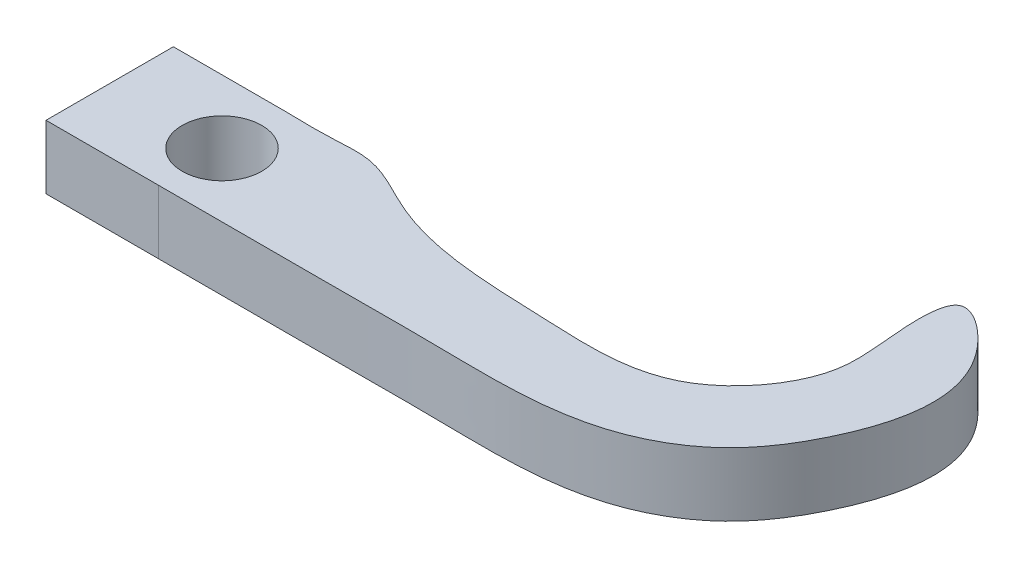
SolidWorks part; units mm, degrees
ref_plane "前视基准面" through (0, 0, 0) normal (0, 0, 1) x (1, 0, 0)
ref_plane "上视基准面" through (0, 0, 0) normal (0, 1, 0) x (1, 0, 0)
ref_plane "右视基准面" through (0, 0, 0) normal (1, 0, 0) x (0, 0, -1)
other "Configuration Table"
sketch "草图1" plane through (0, 0, 0) normal (0, 1, 0) x (1, 0, 0)
  line L0 (0, 4) -> (45, 4) construction
  line L1 (45, 4) -> (45, -4) construction
  line L2 (45, -4) -> (0, -4) construction
  line L3 (45, -4) -> (52.6082, -4) construction
  line L4 (52.6082, -4) -> (52.6082, 16) construction
  line L5 (52.6082, 16) -> (45, 16) construction
  line L6 (45, 16) -> (45, 4) construction
  line L7 (0, 4) -> (-7.0532, 4) construction
  line L8 (-7.0532, 4) -> (-7.0532, -4) construction
  line L9 (-7.0532, -4) -> (0, -4) construction
  line L10 (0, 4) -> (-7.0532, 4)
  line L11 (-7.0532, 4) -> (-7.0532, -4)
  line L12 (-7.0532, -4) -> (0, -4)
  circle A0 centre (0, 0) radius 2.5 construction
  circle A1 centre (0, 0) radius 4 construction
  circle A2 centre (0, 0) radius 2.5
  circle A3 centre (0, 0) radius 4
  spline S0 degree 3 poles (0, 4) (0.9652, 3.9779) (2.6763, 3.9388) (5.7483, 4.2351) (10.7984, 1.043) (18.4189, 0.9833) (27.4063, 0.4151) (31.8486, 6.5096) (31.1785, 10.599) (31.0094, 15.9203) (37.3084, 11.2163) (35.805, 4.5672) (32.4111, -0.6507) (26.4671, -4.264) (18.8603, -3.9418) (11.6431, -4.0066) (5.8074, -3.9976) (2.2358, -3.9991) (0, -4) knots 0 0 0 0 0.031523 0.055887 0.098002 0.21606 0.302294 0.373418 0.416617 0.454315 0.488953 0.591587 0.647126 0.690459 0.810546 0.883819 0.927272 1 1 1 1
  point P16 (18.9299, 2.8554)
  point P18 (9.6052, 4)
  point P20 (4.768, 4)
  point P22 (7.5071, 4)
  point P24 (13.1019, 3.2051)
  point P26 (21.4359, -4)
  point P28 (10.2462, -4)
  point P30 (17.0067, -4)
  point P32 (19.0464, 1.5733)
  point P33 (40.5688, 6.738)
  point P34 (26.3314, 1.6898)
  point P36 (30.8189, 7.9258)
  point P38 (34.6071, 16)
  point P40 (37.8125, 17.5419)
  point P42 (41.0178, 16.8425)
  point P44 (45, 11.4225)
  point P46 (40.174, 14.7334)
  point P47 (32.5734, 13.3515)
  point P48 (35.6334, 17.6947)
  point P49 (38.7921, 16)
  point P50 (37.9037, 9.8967)
  point P51 (35.2386, 2.5922)
  point P52 (30.5005, -1.4548)
  point P53 (28.1315, 2.2961)
  point P54 (33.1657, 15.8192)
  point P55 (35.557, 18.2531)
  point P56 (2.4354, 4)
  point P57 (4.6833, 4)
  point P58 (13.3113, 2.7055)
  point P59 (8.2865, 3.2674)
  point P60 (26.9309, 2.6393)
  point P61 (32.6131, 10.5376)
  point P62 (36.2093, 15.7527)
  point P63 (38.0138, 14.1437)
  point P64 (38.401, 7.4629)
  point P65 (37.764, 7.618)
  point P66 (31.2222, 11.189)
  point P67 (32.8184, 14.4783)
  point P68 (35.0919, 13.801)
  point P69 (36.4463, 7.1741)
  point P70 (35.4305, 12.6885)
  point P71 (0, 0)
  point P72 (33.2054, 15.349)
  point P73 (31.741, 14.6282)
  point P74 (36.3019, 5.9045)
  point P75 (34.4777, 12.9779)
  point P76 (36.153, 5.4578)
  point P77 (28.4934, -2.7921)
  point P78 (0, 0)
  point P79 (33.2224, 0.3529)
  point P80 (35.5495, 4.4673)
  point P81 (31.8841, -0.6738)
  point P82 (34.8354, 3.5153)
  dimension "D1" = 5
  dimension "D2" = 8
  dimension "D3" = 45
  dimension "D4" = 20
extrude "凸台-拉伸1" add sketch "草图1" along normal blind 4 contours A1 A0 | A1 L2 L1 L0 | L5 L6 L1 L3 L4 | A1 L7 L8 L9 | S0 L12 L11 L10 | A2
